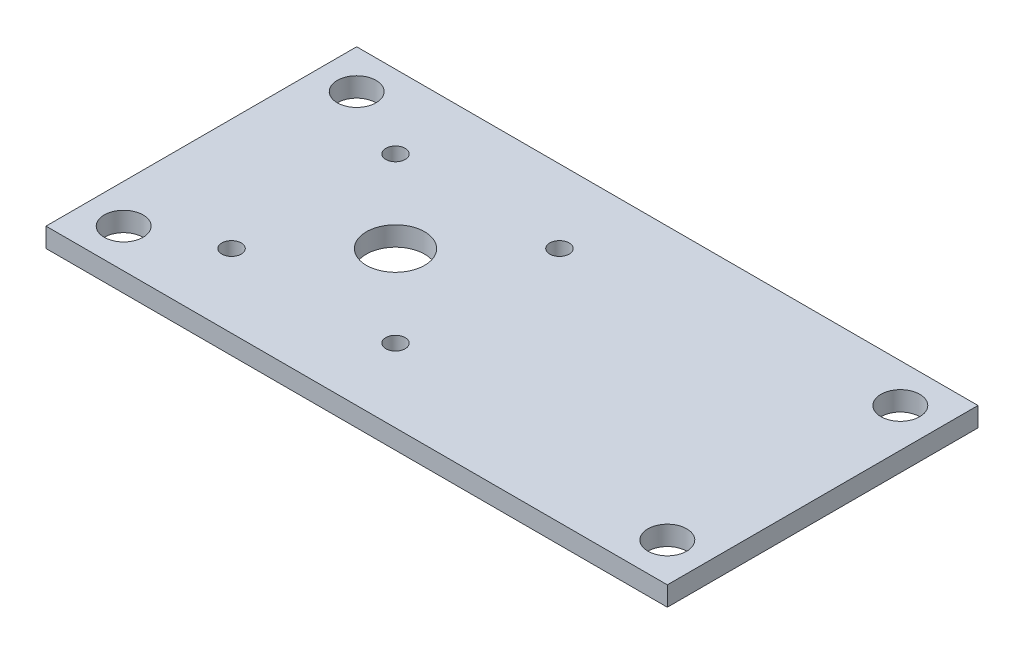
SolidWorks part; units mm, degrees
ref_plane "Front Plane" through (0, 0, 0) normal (0, 0, 1) x (1, 0, 0)
ref_plane "Top Plane" through (0, 0, 0) normal (0, 1, 0) x (1, 0, 0)
ref_plane "Right Plane" through (0, 0, 0) normal (1, 0, 0) x (0, 0, -1)
sketch "Sketch1" plane through (0, 0, 0) normal (0, 1, 0) x (1, 0, 0)
  line L1 (0, 0) -> (203.2, 0)
  line L2 (0, 0) -> (0, 101.6)
  line L3 (0, 101.6) -> (203.2, 101.6)
  line L4 (203.2, 0) -> (203.2, 101.6)
  dimension "D1" = 101.6
  dimension "D2" = 203.2
extrude "Boss-Extrude1" add sketch "Sketch1" along normal blind 6.35
sketch "Sketch2" plane through (0, 6.35, 0) normal (0, 1, 0) x (1, 0, 0)
  line L0 (0, 50.8) -> (63.5, 50.8) construction
  line L1 (0, 101.6) -> (0, 0) construction
  line L2 (63.5, 50.8) -> (63.5, 101.6) construction
  line L3 (203.2, 101.6) -> (0, 101.6) construction
  circle A0 centre (63.5, 50.8) radius 9.525
  circle A1 centre (123.82, 50.8) radius 5 construction
  dimension "D1" = 10
  dimension "D2" = 19.05
  dimension "D3" = 63.5
  dimension "D4" = 60.32
extrude "Cut-Extrude1" cut sketch "Sketch2" against normal through all
sketch "Sketch3" plane through (0, 6.35, 0) normal (0, 1, 0) x (1, 0, 0)
  line L0 (0, 88.9) -> (12.7, 88.9) construction
  line L1 (0, 101.6) -> (0, 0) construction
  line L2 (12.7, 88.9) -> (12.7, 101.6) construction
  line L3 (203.2, 101.6) -> (0, 101.6) construction
  circle A0 centre (12.7, 88.9) radius 6.35
  dimension "D1" = 12.7
  dimension "D2" = 12.7
extrude "Cut-Extrude2" cut sketch "Sketch3" against normal through all
ref_plane "Plane1" through (101.6, 0, 0) normal (-1, 0, 0) x (0, 0, 1)
ref_plane "Plane2" through (0, 0, -50.8) normal (0, 0, 1) x (1, 0, 0)
mirror "Mirror1" about plane through (0, 0, -50.8) normal (0, 0, 1) of "Cut-Extrude2"
mirror "Mirror2" about plane through (101.6, 0, 0) normal (-1, 0, 0) of "Mirror1", "Cut-Extrude2"
sketch "Sketch4" plane through (0, 6.35, 0) normal (0, 1, 0) x (1, 0, 0)
  line L0 (36.6939, 77.6061) -> (63.5, 50.8) construction
  line L1 (63.5, 50.8) -> (0, 50.8) construction
  line L2 (-3.4925, 50.8) -> (3.4925, 50.8) construction
  circle A0 centre (36.6939, 77.6061) radius 3.175
  point P2 (63.5, 50.8)
  dimension "D1" = 6.35
  dimension "D2" = 37.9095
  dimension "D3" = 45
extrude "Cut-Extrude3" cut sketch "Sketch4" against normal through all
pattern_circular "CirPattern1" count 4 over 360 about axis through (63.5, 0, -50.8) along (0, 1, 0) of "Cut-Extrude3"
sketch "Sketch5" plane through (0, 6.35, 0) normal (0, 1, 0) x (1, 0, 0)
  circle A0 centre (63.5, 50.8) radius 50.8
  circle A1 centre (12.7, 88.9) radius 13.4937
  dimension "D1" = 26.9875
  dimension "D2" = 101.6
equation "\"D2@Sketch4\"=(3.27+2.7)/4*25.4"
